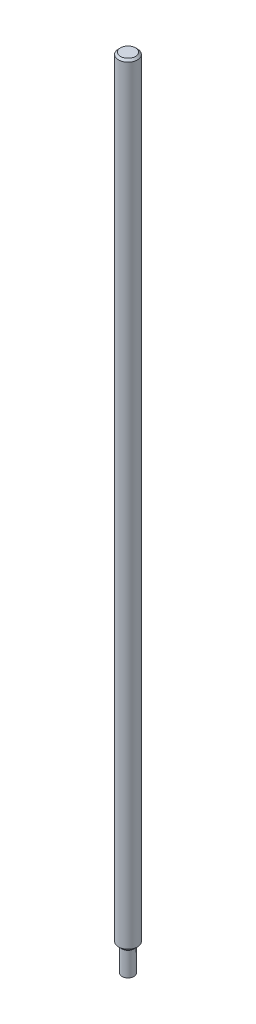
SolidWorks part; units mm, degrees
ref_plane "Front Plane" through (0, 0, 0) normal (0, 0, 1) x (1, 0, 0)
ref_plane "Top Plane" through (0, 0, 0) normal (0, 1, 0) x (1, 0, 0)
ref_plane "Right Plane" through (0, 0, 0) normal (1, 0, 0) x (0, 0, -1)
sketch "Sketch1" plane through (0, 0, 0) normal (1, 0, 0) x (0, 0, -1)
  line L0 (0, 100) -> (0, -100)
  line L1 (-2.38, -93.12) -> (-2.38, 100)
  line L2 (-2.38, 100) -> (0, 100)
  line L3 (0, -100) -> (-1.5, -100)
  line L4 (-1.5, -100) -> (-1.5, -94)
  line L5 (-1.5, -94) -> (-2.38, -93.12)
  point P7 (0, 0)
  dimension "D1" = 2.38
  dimension "D2" = 135
  dimension "D3" = 1.5
  dimension "D4" = 6
  dimension "D5" = 200
revolve "Revolve1" add sketch "Sketch1" angle 360 about L0
chamfer "Chamfer1" distance 0.5 angle 45 1 edges at (0, 100, 2.38)
